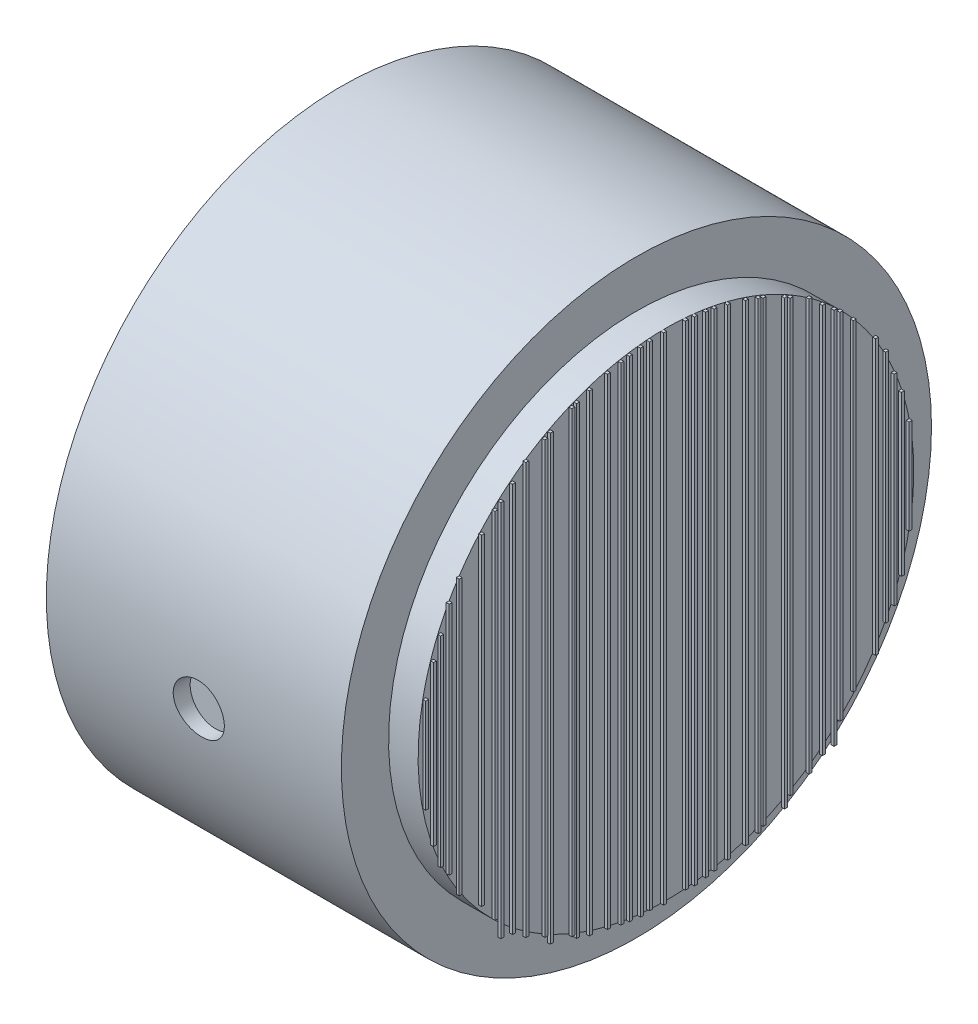
SolidWorks part; units mm, degrees
material "Cast Alloy Steel"
ref_plane "Front Plane" through (0, 0, 0) normal (0, 0, 1) x (1, 0, 0)
ref_plane "Top Plane" through (0, 0, 0) normal (0, 1, 0) x (1, 0, 0)
ref_plane "Right Plane" through (0, 0, 0) normal (1, 0, 0) x (0, 0, -1)
sketch "Sketch7" plane through (0, 0, 0) normal (1, 0, 0) x (0, 0, -1)
  line L0 (0, 973.5) -> (0, -973.5) construction
  circle A0 centre (0, 2580) radius 1000
  dimension "D1" = 2000
extrude "Light Cylinder" add sketch "Sketch7" along normal mid plane 1000 separate body
sketch "Sketch8" plane through (500, 0, 0) normal (1, 0, 0) x (0, 0, -1)
  circle A0 centre (0, 2580) radius 840
  dimension "D1" = 1680
extrude "Window" add sketch "Sketch8" along normal blind 100
sketch "Sketch9" plane through (600, 0, 0) normal (1, 0, 0) x (0, 0, -1)
  line L0 (0, 1740) -> (0, 3772.0471) construction
  line L1 (-824.1597, 2742.3602) -> (-814.1597, 2742.3602)
  line L2 (-824.1597, 2742.3602) -> (-824.1597, 2421.851)
  line L3 (-824.1597, 2421.851) -> (-814.1597, 2421.851)
  line L4 (-814.1597, 2742.3602) -> (-814.1597, 2421.851)
  line L5 (-798.0268, 2842.2083) -> (-788.0268, 2842.2083)
  line L6 (-798.0268, 2842.2083) -> (-798.0268, 2302.2083)
  line L7 (-798.0268, 2302.2083) -> (-788.0268, 2302.2083)
  line L8 (-788.0268, 2842.2083) -> (-788.0268, 2302.2083)
  line L9 (-773.3567, 2907.9016) -> (-763.3567, 2907.9016)
  line L10 (-773.3567, 2907.9016) -> (-773.3567, 2227.9016)
  line L11 (-773.3567, 2227.9016) -> (-763.3567, 2227.9016)
  line L12 (-763.3567, 2907.9016) -> (-763.3567, 2227.9016)
  line L13 (-17.8902, 3419.8095) -> (-7.8902, 3419.8095)
  line L14 (-17.8902, 3419.8095) -> (-17.8902, 1740.0371)
  line L15 (-17.8902, 1740.0371) -> (-7.8902, 1740.0371)
  line L16 (-7.8902, 3419.8095) -> (-7.8902, 1740.0371)
  line L17 (-700.6615, 3043.3287) -> (-710.6615, 3043.3287)
  line L18 (-700.6615, 3043.3287) -> (-700.6615, 2113.9665)
  line L19 (-700.6615, 2113.9665) -> (-710.6615, 2113.9665)
  line L20 (-710.6615, 3043.3287) -> (-710.6615, 2113.9665)
  line L21 (-734.8073, 2987.0114) -> (-744.8073, 2987.0114)
  line L22 (-734.8073, 2987.0114) -> (-734.8073, 2191.5903)
  line L23 (-734.8073, 2191.5903) -> (-744.8073, 2191.5903)
  line L24 (-744.8073, 2987.0114) -> (-744.8073, 2191.5903)
  line L25 (-624.7617, 3134.5449) -> (-634.7617, 3134.5449)
  line L26 (-624.7617, 3134.5449) -> (-624.7617, 2044.5449)
  line L27 (-624.7617, 2044.5449) -> (-634.7617, 2044.5449)
  line L28 (-634.7617, 3134.5449) -> (-634.7617, 2044.5449)
  line L29 (-579.4942, 3181.5882) -> (-589.4942, 3181.5882)
  line L30 (-579.4942, 3181.5882) -> (-579.4942, 1981.5882)
  line L31 (-579.4942, 1981.5882) -> (-589.4942, 1981.5882)
  line L32 (-589.4942, 3181.5882) -> (-589.4942, 1981.5882)
  line L33 (-569.5636, 3197.4118) -> (-559.5636, 3197.4118)
  line L34 (-569.5636, 3197.4118) -> (-569.5636, 1917.4118)
  line L35 (-569.5636, 1917.4118) -> (-559.5636, 1917.4118)
  line L36 (-559.5636, 3197.4118) -> (-559.5636, 1917.4118)
  line L37 (-530.0486, 3231.6505) -> (-520.0486, 3231.6505)
  line L38 (-530.0486, 3231.6505) -> (-530.0486, 1909.7825)
  line L39 (-530.0486, 1909.7825) -> (-520.0486, 1909.7825)
  line L40 (-520.0486, 3231.6505) -> (-520.0486, 1909.7825)
  line L41 (-474.9646, 3272.8266) -> (-484.9646, 3272.8266)
  line L42 (-474.9646, 3272.8266) -> (-474.9646, 1878.1806)
  line L43 (-474.9646, 1878.1806) -> (-484.9646, 1878.1806)
  line L44 (-484.9646, 3272.8266) -> (-484.9646, 1878.1806)
  line L45 (-420.5321, 3307.1539) -> (-410.5321, 3307.1539)
  line L46 (-420.5321, 3307.1539) -> (-420.5321, 1847.1539)
  line L47 (-420.5321, 1847.1539) -> (-410.5321, 1847.1539)
  line L48 (-410.5321, 3307.1539) -> (-410.5321, 1847.1539)
  line L49 (-401.9316, 3317.5981) -> (-391.9316, 3317.5981)
  line L50 (-401.9316, 3317.5981) -> (-401.9316, 1817.5981)
  line L51 (-401.9316, 1817.5981) -> (-391.9316, 1817.5981)
  line L52 (-391.9316, 3317.5981) -> (-391.9316, 1817.5981)
  line L53 (-328.9531, 3352.91) -> (-318.9531, 3352.91)
  line L54 (-328.9531, 3352.91) -> (-328.9531, 1802.91)
  line L55 (-328.9531, 1802.91) -> (-318.9531, 1802.91)
  line L56 (-318.9531, 3352.91) -> (-318.9531, 1802.91)
  line L57 (-312.5333, 3359.6941) -> (-302.5333, 3359.6941)
  line L58 (-312.5333, 3359.6941) -> (-312.5333, 1789.6941)
  line L59 (-312.5333, 1789.6941) -> (-302.5333, 1789.6941)
  line L60 (-302.5333, 3359.6941) -> (-302.5333, 1789.6941)
  line L61 (-269.6186, 3375.5538) -> (-259.6186, 3375.5538)
  line L62 (-269.6186, 3375.5538) -> (-269.6186, 1775.5538)
  line L63 (-269.6186, 1775.5538) -> (-259.6186, 1775.5538)
  line L64 (-259.6186, 3375.5538) -> (-259.6186, 1775.5538)
  line L65 (-208.3432, 3393.7525) -> (-198.3432, 3393.7525)
  line L66 (-208.3432, 3393.7525) -> (-208.3432, 1763.7525)
  line L67 (-208.3432, 1763.7525) -> (-198.3432, 1763.7525)
  line L68 (-198.3432, 3393.7525) -> (-198.3432, 1763.7525)
  line L69 (-162.9528, 3404.0427) -> (-152.9528, 3404.0427)
  line L70 (-162.9528, 3404.0427) -> (-162.9528, 1754.0427)
  line L71 (-162.9528, 1754.0427) -> (-152.9528, 1754.0427)
  line L72 (-152.9528, 3404.0427) -> (-152.9528, 1754.0427)
  line L73 (-134.1294, 3409.2221) -> (-124.1294, 3409.2221)
  line L74 (-134.1294, 3409.2221) -> (-134.1294, 1749.2221)
  line L75 (-134.1294, 1749.2221) -> (-124.1294, 1749.2221)
  line L76 (-124.1294, 3409.2221) -> (-124.1294, 1749.2221)
  line L77 (-96.3767, 3414.4528) -> (-86.3767, 3414.4528)
  line L78 (-96.3767, 3414.4528) -> (-96.3767, 1744.4528)
  line L79 (-96.3767, 1744.4528) -> (-86.3767, 1744.4528)
  line L80 (-86.3767, 3414.4528) -> (-86.3767, 1744.4528)
  line L81 (-65.7639, 3417.4217) -> (-55.7639, 3417.4217)
  line L82 (-65.7639, 3417.4217) -> (-65.7639, 1747.4217)
  line L83 (-65.7639, 1747.4217) -> (-55.7639, 1747.4217)
  line L84 (-55.7639, 3417.4217) -> (-55.7639, 1747.4217)
  line L85 (55.7639, 3417.4217) -> (55.7639, 1747.4217)
  line L86 (65.7639, 1747.4217) -> (55.7639, 1747.4217)
  line L87 (65.7639, 3417.4217) -> (65.7639, 1747.4217)
  line L88 (65.7639, 3417.4217) -> (55.7639, 3417.4217)
  line L89 (86.3767, 3414.4528) -> (86.3767, 1744.4528)
  line L90 (96.3767, 1744.4528) -> (86.3767, 1744.4528)
  line L91 (96.3767, 3414.4528) -> (96.3767, 1744.4528)
  line L92 (96.3767, 3414.4528) -> (86.3767, 3414.4528)
  line L93 (124.1294, 3409.2221) -> (124.1294, 1749.2221)
  line L94 (134.1294, 1749.2221) -> (124.1294, 1749.2221)
  line L95 (134.1294, 3409.2221) -> (134.1294, 1749.2221)
  line L96 (134.1294, 3409.2221) -> (124.1294, 3409.2221)
  line L97 (152.9528, 3404.0427) -> (152.9528, 1754.0427)
  line L98 (162.9528, 1754.0427) -> (152.9528, 1754.0427)
  line L99 (162.9528, 3404.0427) -> (162.9528, 1754.0427)
  line L100 (162.9528, 3404.0427) -> (152.9528, 3404.0427)
  line L101 (198.3432, 3393.7525) -> (198.3432, 1763.7525)
  line L102 (208.3432, 1763.7525) -> (198.3432, 1763.7525)
  line L103 (208.3432, 3393.7525) -> (208.3432, 1763.7525)
  line L104 (208.3432, 3393.7525) -> (198.3432, 3393.7525)
  line L105 (259.6186, 3375.5538) -> (259.6186, 1775.5538)
  line L106 (269.6186, 1775.5538) -> (259.6186, 1775.5538)
  line L107 (269.6186, 3375.5538) -> (269.6186, 1775.5538)
  line L108 (269.6186, 3375.5538) -> (259.6186, 3375.5538)
  line L109 (302.5333, 3359.6941) -> (302.5333, 1789.6941)
  line L110 (312.5333, 1789.6941) -> (302.5333, 1789.6941)
  line L111 (312.5333, 3359.6941) -> (312.5333, 1789.6941)
  line L112 (312.5333, 3359.6941) -> (302.5333, 3359.6941)
  line L113 (318.9531, 3352.91) -> (318.9531, 1802.91)
  line L114 (328.9531, 1802.91) -> (318.9531, 1802.91)
  line L115 (328.9531, 3352.91) -> (328.9531, 1802.91)
  line L116 (328.9531, 3352.91) -> (318.9531, 3352.91)
  line L117 (391.9316, 3317.5981) -> (391.9316, 1817.5981)
  line L118 (401.9316, 1817.5981) -> (391.9316, 1817.5981)
  line L119 (401.9316, 3317.5981) -> (401.9316, 1817.5981)
  line L120 (401.9316, 3317.5981) -> (391.9316, 3317.5981)
  line L121 (410.5321, 3307.1539) -> (410.5321, 1847.1539)
  line L122 (420.5321, 1847.1539) -> (410.5321, 1847.1539)
  line L123 (420.5321, 3307.1539) -> (420.5321, 1847.1539)
  line L124 (420.5321, 3307.1539) -> (410.5321, 3307.1539)
  line L125 (484.9646, 3272.8266) -> (484.9646, 1878.1806)
  line L126 (474.9646, 1878.1806) -> (484.9646, 1878.1806)
  line L127 (474.9646, 3272.8266) -> (474.9646, 1878.1806)
  line L128 (474.9646, 3272.8266) -> (484.9646, 3272.8266)
  line L129 (520.0486, 3231.6505) -> (520.0486, 1909.7825)
  line L130 (530.0486, 1909.7825) -> (520.0486, 1909.7825)
  line L131 (530.0486, 3231.6505) -> (530.0486, 1909.7825)
  line L132 (530.0486, 3231.6505) -> (520.0486, 3231.6505)
  line L133 (559.5636, 3197.4118) -> (559.5636, 1917.4118)
  line L134 (569.5636, 1917.4118) -> (559.5636, 1917.4118)
  line L135 (569.5636, 3197.4118) -> (569.5636, 1917.4118)
  line L136 (569.5636, 3197.4118) -> (559.5636, 3197.4118)
  line L137 (589.4942, 3181.5882) -> (589.4942, 1981.5882)
  line L138 (579.4942, 1981.5882) -> (589.4942, 1981.5882)
  line L139 (579.4942, 3181.5882) -> (579.4942, 1981.5882)
  line L140 (579.4942, 3181.5882) -> (589.4942, 3181.5882)
  line L141 (634.7617, 3134.5449) -> (634.7617, 2044.5449)
  line L142 (624.7617, 2044.5449) -> (634.7617, 2044.5449)
  line L143 (624.7617, 3134.5449) -> (624.7617, 2044.5449)
  line L144 (624.7617, 3134.5449) -> (634.7617, 3134.5449)
  line L145 (744.8073, 2987.0114) -> (744.8073, 2191.5903)
  line L146 (734.8073, 2191.5903) -> (744.8073, 2191.5903)
  line L147 (734.8073, 2987.0114) -> (734.8073, 2191.5903)
  line L148 (734.8073, 2987.0114) -> (744.8073, 2987.0114)
  line L149 (710.6615, 3043.3287) -> (710.6615, 2113.9665)
  line L150 (700.6615, 2113.9665) -> (710.6615, 2113.9665)
  line L151 (700.6615, 3043.3287) -> (700.6615, 2113.9665)
  line L152 (700.6615, 3043.3287) -> (710.6615, 3043.3287)
  line L153 (763.3567, 2907.9016) -> (763.3567, 2227.9016)
  line L154 (773.3567, 2227.9016) -> (763.3567, 2227.9016)
  line L155 (773.3567, 2907.9016) -> (773.3567, 2227.9016)
  line L156 (773.3567, 2907.9016) -> (763.3567, 2907.9016)
  line L157 (788.0268, 2842.2083) -> (788.0268, 2302.2083)
  line L158 (798.0268, 2302.2083) -> (788.0268, 2302.2083)
  line L159 (798.0268, 2842.2083) -> (798.0268, 2302.2083)
  line L160 (798.0268, 2842.2083) -> (788.0268, 2842.2083)
  line L161 (814.1597, 2742.3602) -> (814.1597, 2421.851)
  line L162 (824.1597, 2421.851) -> (814.1597, 2421.851)
  line L163 (824.1597, 2742.3602) -> (824.1597, 2421.851)
  line L164 (824.1597, 2742.3602) -> (814.1597, 2742.3602)
  circle A0 centre (0, 2580) radius 840 construction
  circle A1 centre (0, 2580) radius 840 construction
  dimension "D1" = 10
  dimension "D2" = 540
  dimension "D3" = 10
  dimension "D4" = 680
  dimension "D5" = 10
  dimension "D6" = 1679.7724
  dimension "D7" = 10
  dimension "D8" = 1090
  dimension "D9" = 10
  dimension "D10" = 10
  dimension "D11" = 10
  dimension "D12" = 1200
  dimension "D13" = 10
  dimension "D14" = 1280
  dimension "D15" = 10
  dimension "D16" = 10
  dimension "D17" = 10
  dimension "D18" = 1460
  dimension "D19" = 10
  dimension "D20" = 1500
  dimension "D21" = 10
  dimension "D22" = 1550
  dimension "D23" = 10
  dimension "D24" = 1570
  dimension "D25" = 10
  dimension "D26" = 1600
  dimension "D27" = 10
  dimension "D28" = 1630
  dimension "D29" = 10
  dimension "D30" = 1650
  dimension "D31" = 10
  dimension "D32" = 1660
  dimension "D33" = 10
  dimension "D34" = 1670
  dimension "D35" = 10
  dimension "D36" = 1670
  dimension "D37" = 10
sketch "Window CrossBar" plane through (600, 0, 0) normal (1, 0, 0) x (0, 0, -1)
  line L1 (-839.9994, 2579.006) -> (839.773, 2579.006)
  line L2 (-839.9994, 2579.006) -> (-839.9994, 2599.5292)
  line L3 (-839.9994, 2599.5292) -> (839.773, 2599.5292)
  line L4 (839.773, 2579.006) -> (839.773, 2599.5292)
  circle A1 centre (0, 2580) radius 840 construction
  circle A2 centre (0, 2580) radius 840 construction
extrude "Window Bars" add sketch "Sketch9" along normal blind 10
ref_plane "Plane1" through (0, 0, -1000) normal (0, 0, -1) x (-1, 0, 0)
sketch "Sketch10" plane through (0, 0, -1000) normal (0, 0, -1) x (-1, 0, 0)
  circle A0 centre (-13.9154, 2507.1875) radius 87.5
  dimension "D1" = 175
ref_plane "Plane2" through (0, 0, 1000) normal (0, 0, 1) x (1, 0, 0)
extrude "Cut-Extrude3" cut sketch "Sketch10" against normal blind 60
sketch "Sketch16" plane through (0, 0, 1000) normal (0, 0, 1) x (1, 0, 0)
  circle A0 centre (13.9154, 2507.1875) radius 86.4531
extrude "Cut-Extrude4" cut sketch "Sketch16" against normal blind 60
